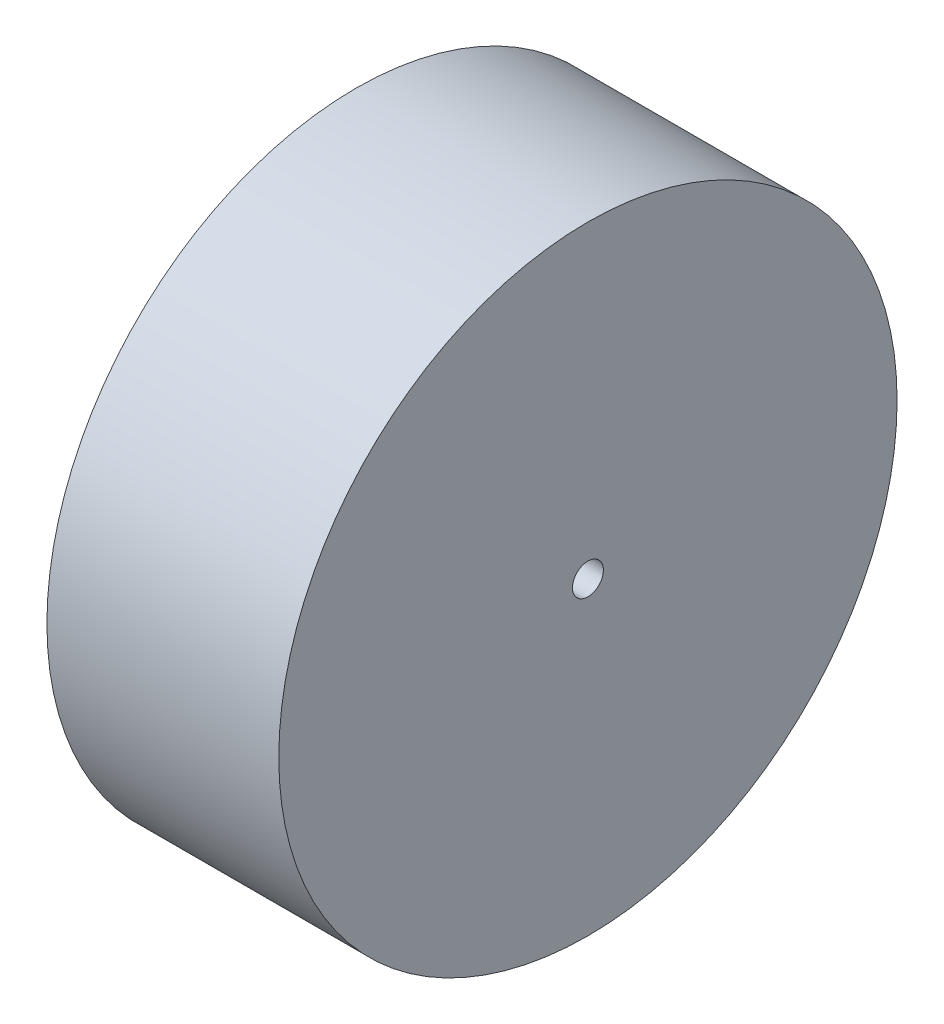
SolidWorks part; units mm, degrees
material "AISI 1020 Steel, Cold Rolled"
ref_plane "Front Plane" through (0, 0, 0) normal (1, 0, 0) x (0, 1, 0)
ref_plane "Top Plane" through (0, 0, 0) normal (0, 0, 1) x (0, 1, 0)
ref_plane "Right Plane" through (0, 0, 0) normal (0, 1, 0) x (-1, 0, 0)
sketch "Sketch1" plane through (0, 0, 0) normal (1, 0, 0) x (0, 1, 0)
  circle A0 centre (0, 0) radius 25.4
  circle A1 centre (0, 0) radius 1.27
  dimension "D1" = 50.8
  dimension "D2" = 2.54
extrude "Boss-Extrude1" add sketch "Sketch1" along normal mid plane 19.05
